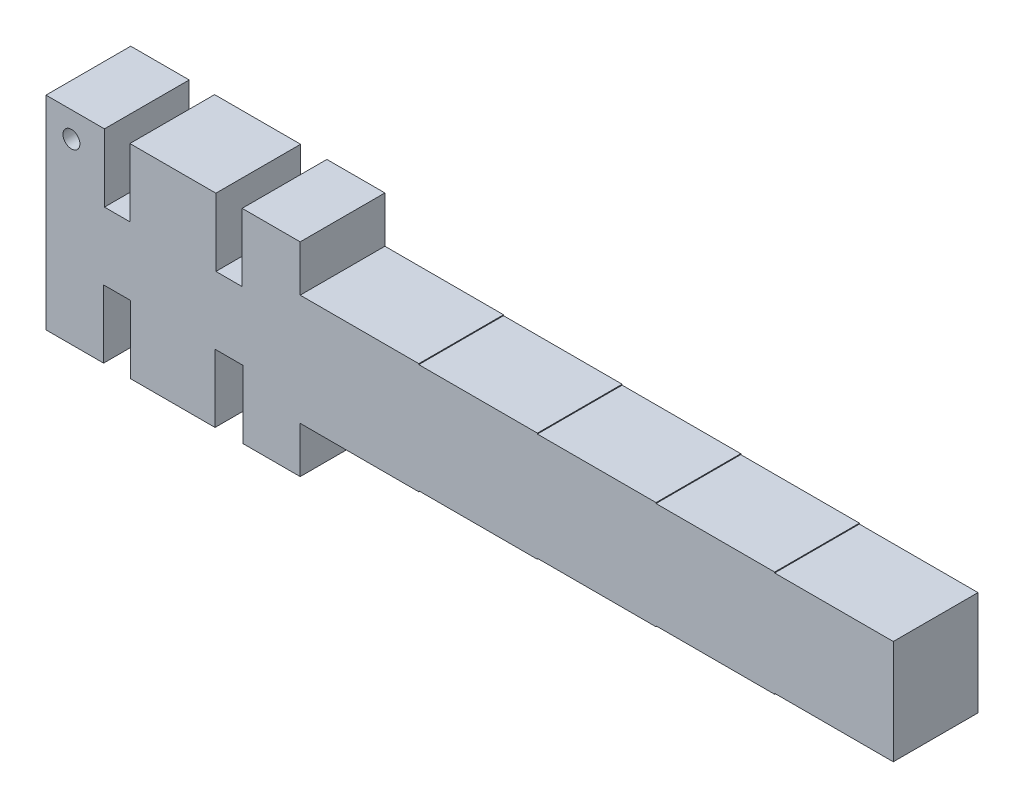
SolidWorks part; units mm, degrees
ref_plane "Front Plane" through (0, 0, 0) normal (0, 0, 1) x (1, 0, 0)
ref_plane "Top Plane" through (0, 0, 0) normal (0, 1, 0) x (1, 0, 0)
ref_plane "Right Plane" through (0, 0, 0) normal (1, 0, 0) x (0, 0, -1)
ref_plane "PZ 5.000" through (0, 0, 5) normal (0, 0, 1) x (1, 0, 0)
sketch "gauge body sketch" plane through (0, 0, 5) normal (0, 0, 1) x (1, 0, 0)
  line L0 (-30, 12) -> (0, 12)
  line L1 (0, 12) -> (0, 6.55)
  line L2 (0, 6.55) -> (14, 6.55)
  line L3 (14, 6.55) -> (14, 6.45)
  line L4 (14, 6.45) -> (28, 6.45)
  line L5 (28, 6.45) -> (28, 6.35)
  line L6 (28, 6.35) -> (42, 6.35)
  line L7 (42, 6.35) -> (42, 6.25)
  line L8 (42, 6.25) -> (56, 6.25)
  line L9 (56, 6.25) -> (56, 6.15)
  line L10 (56, 6.15) -> (70, 6.15)
  line L11 (70, 6.15) -> (70, -6.15)
  line L12 (70, -6.15) -> (56, -6.15)
  line L13 (56, -6.15) -> (56, -6.25)
  line L14 (56, -6.25) -> (42, -6.25)
  line L15 (42, -6.25) -> (42, -6.35)
  line L16 (42, -6.35) -> (28, -6.35)
  line L17 (28, -6.35) -> (28, -6.45)
  line L18 (28, -6.45) -> (14, -6.45)
  line L19 (14, -6.45) -> (14, -6.55)
  line L20 (14, -6.55) -> (0, -6.55)
  line L21 (0, -6.55) -> (0, -12)
  line L22 (0, -12) -> (-30, -12)
  line L23 (-30, -12) -> (-30, 12)
extrude "gauge body" add sketch "gauge body sketch" along normal mid plane 10
sketch "notch 3.0 sketch" plane through (0, 0, 5) normal (0, 0, 1) x (1, 0, 0)
  line L0 (-23.1, 4) -> (-20.1, 4)
  line L1 (-20.1, 4) -> (-20.1, 13)
  line L2 (-20.1, 13) -> (-23.1, 13)
  line L3 (-23.1, 13) -> (-23.1, 4)
extrude "notch 3.0" cut sketch "notch 3.0 sketch" against normal mid plane 12
sketch "notch 3.1 sketch" plane through (0, 0, 5) normal (0, 0, 1) x (1, 0, 0)
  line L0 (-9.95, 4) -> (-6.85, 4)
  line L1 (-6.85, 4) -> (-6.85, 13)
  line L2 (-6.85, 13) -> (-9.95, 13)
  line L3 (-9.95, 13) -> (-9.95, 4)
extrude "notch 3.1" cut sketch "notch 3.1 sketch" against normal mid plane 12
sketch "notch 3.2 sketch" plane through (0, 0, 5) normal (0, 0, 1) x (1, 0, 0)
  line L0 (-23.2, -13) -> (-20, -13)
  line L1 (-20, -13) -> (-20, -4)
  line L2 (-20, -4) -> (-23.2, -4)
  line L3 (-23.2, -4) -> (-23.2, -13)
extrude "notch 3.2" cut sketch "notch 3.2 sketch" against normal mid plane 12
sketch "notch 3.3 sketch" plane through (0, 0, 5) normal (0, 0, 1) x (1, 0, 0)
  line L0 (-10.05, -13) -> (-6.75, -13)
  line L1 (-6.75, -13) -> (-6.75, -4)
  line L2 (-6.75, -4) -> (-10.05, -4)
  line L3 (-10.05, -4) -> (-10.05, -13)
extrude "notch 3.3" cut sketch "notch 3.3 sketch" against normal mid plane 12
sketch "mark hole sketch" plane through (0, 0, 5) normal (0, 0, 1) x (1, 0, 0)
  circle A0 centre (-27, 9) radius 1
extrude "mark hole" cut sketch "mark hole sketch" against normal mid plane 12
equation "\"diffL\" = 608.8mm"
equation "\"diffW\" = 329.4mm"
equation "\"diffT\" = 2.9mm"
equation "\"chanSlotW\" = 12.8mm"
equation "\"chanSlotDepth\" = 11.13mm"
equation "\"chanFloor\" = 1.57mm"
equation "\"chanLeg\" = 12.7mm"
equation "\"lightL\" = 605mm"
equation "\"lightW\" = 330mm"
equation "\"lightH\" = 92mm"
equation "\"gaugeH\" = 10mm"
equation "\"gaugeStepLen\" = 14mm"
equation "\"gaugeStepW0\" = 13.1mm"
equation "\"gaugeStepDW\" = 0.2mm"
equation "\"gaugeSteps\" = 5mm"
equation "\"gaugeHandleLen\" = 30mm"
equation "\"gaugeHandleW\" = 24mm"
equation "\"gaugeSlot0\" = 3mm"
equation "\"gaugeSlotD\" = 0.1mm"
equation "\"gaugeSlotDepth\" = 8mm"
